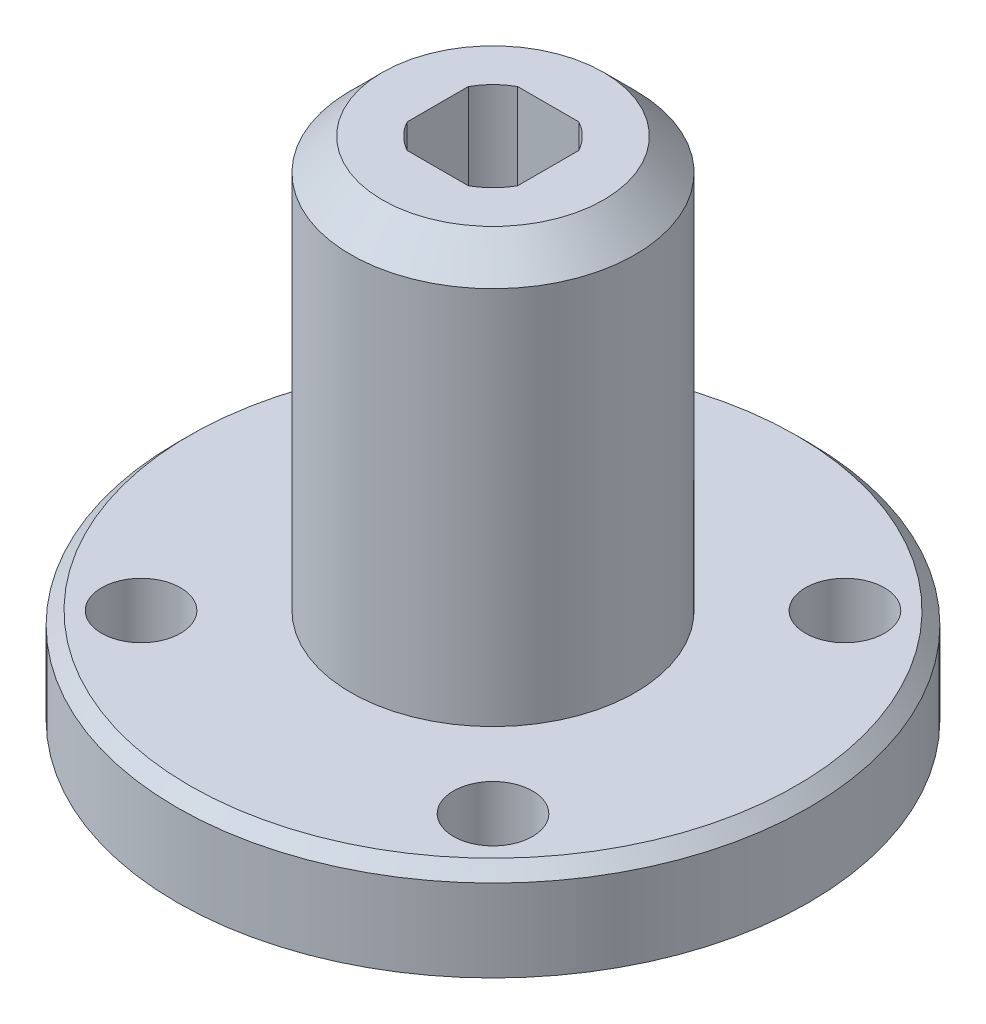
SolidWorks part; units mm, degrees
ref_plane "Front" through (0, 0, 0) normal (0, 0, 1) x (1, 0, 0)
ref_plane "Top" through (0, 0, 0) normal (0, 1, 0) x (1, 0, 0)
ref_plane "Right" through (0, 0, 0) normal (1, 0, 0) x (0, 0, -1)
sketch "草图1" plane through (0, 0, 0) normal (0, 1, 0) x (1, 0, 0)
  line L0 (-11.1369, 11.1369) -> (0, 0) construction
  circle A0 centre (0, 0) radius 20
  circle A1 centre (-11.1369, 11.1369) radius 2.5
  circle A2 centre (11.1369, 11.1369) radius 2.5
  circle A3 centre (11.1369, -11.1369) radius 2.5
  circle A4 centre (-11.1369, -11.1369) radius 2.5
  point P14 (0, 0)
  dimension "D1" = 40
  dimension "D2" = 5
  dimension "D3" = 15.75
  dimension "D4" = 4
extrude "凸台-拉伸1" add sketch "草图1" along normal blind 6
sketch "草图2" plane through (0, 6, 0) normal (0, 1, 0) x (1, 0, 0)
  line L1 (1.9365, 3.5) -> (-1.9365, 3.5)
  line L2 (3.5, 1.9365) -> (3.5, -1.9365)
  line L3 (1.9365, -3.5) -> (-1.9365, -3.5)
  line L4 (-3.5, 1.9365) -> (-3.5, -1.9365)
  line L5 (3.5, 3.5) -> (-3.5, -3.5) construction
  line L6 (3.5, -3.5) -> (-3.5, 3.5) construction
  circle A0 centre (0, 0) radius 9
  arc A1 (-1.9365, 3.5) -> (-3.5, 1.9365) centre (0, 0) ccw
  arc A2 (-3.5, -1.9365) -> (-1.9365, -3.5) centre (0, 0) ccw
  arc A3 (1.9365, -3.5) -> (3.5, -1.9365) centre (0, 0) ccw
  arc A4 (3.5, 1.9365) -> (1.9365, 3.5) centre (0, 0) ccw
  dimension "D1" = 18
  dimension "D2" = 8
  dimension "D3" = 7
  dimension "D4" = 7
extrude "凸台-拉伸2" add sketch "草图2" along normal blind 26
chamfer "倒角1" distance 0.8 angle 45 1 edges at (0, 6, 20)
chamfer "倒角2" distance 2 angle 45 1 edges at (0, 32, 9)
